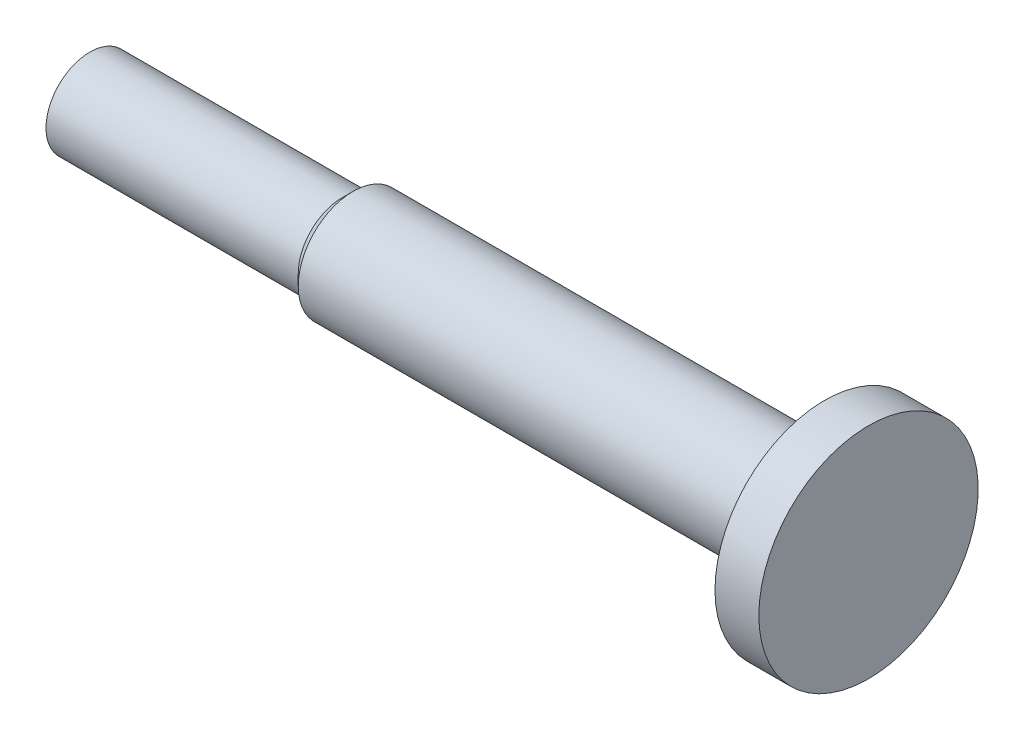
SolidWorks part; units mm, degrees
material "6061 合金"
ref_plane "前视基准面" through (0, 0, 0) normal (0, 0, 1) x (1, 0, 0)
ref_plane "上视基准面" through (0, 0, 0) normal (0, 1, 0) x (1, 0, 0)
ref_plane "右视基准面" through (0, 0, 0) normal (1, 0, 0) x (0, 0, -1)
ref_plane "基准面1" through (0, 0, 0) normal (0, 0, 1) x (1, 0, 0)
sketch "草图1" plane through (0, 0, 0) normal (0, 0, 1) x (1, 0, 0)
  line L0 (-12, 0) -> (-12, 2)
  line L1 (-12, 2) -> (-0.5, 2)
  line L2 (-0.5, 2) -> (0, 2.5)
  line L3 (0, 2.5) -> (21.5, 2.5)
  line L4 (21.5, 2.5) -> (21.5, 5)
  line L5 (21.5, 5) -> (23.5, 5)
  line L6 (23.5, 5) -> (23.5, 0)
  line L7 (23.5, 0) -> (-12, 0)
  line L8 (23.5, 0) -> (-12, 0) construction
revolve "旋转1" add sketch "草图1" angle 360 about L8
cosmetic thread "装饰螺纹线1"
